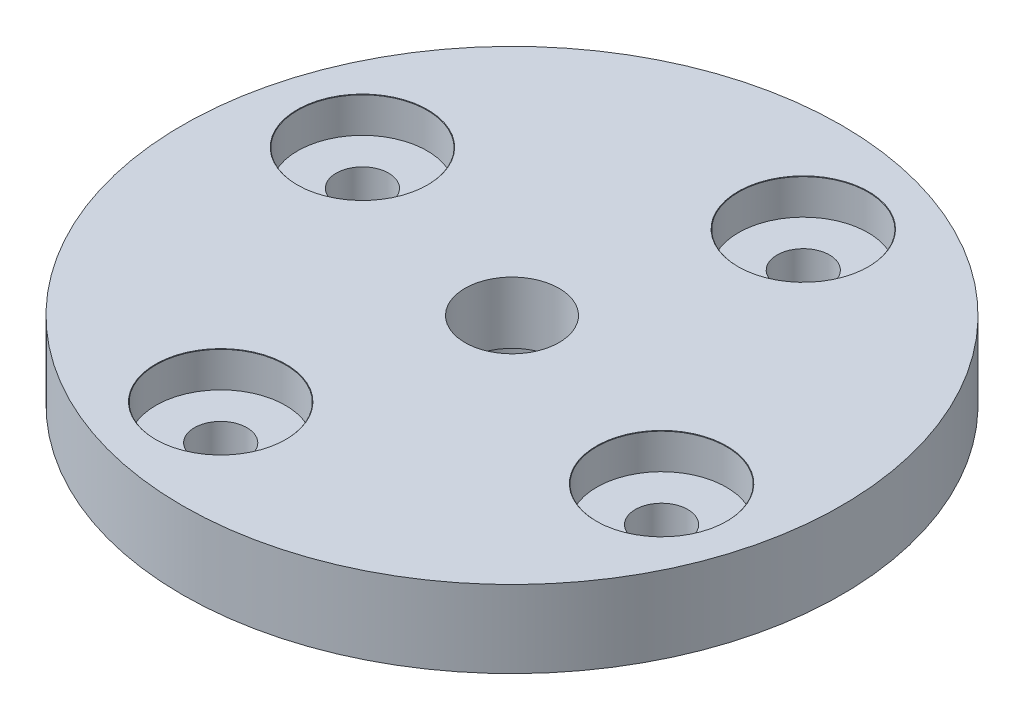
SolidWorks part; units mm, degrees
ref_plane "Front Plane" through (0, 0, 0) normal (0, 0, 1) x (1, 0, 0)
ref_plane "Top Plane" through (0, 0, 0) normal (0, 1, 0) x (1, 0, 0)
ref_plane "Right Plane" through (0, 0, 0) normal (1, 0, 0) x (0, 0, -1)
sketch "Sketch1" plane through (0, 0, 0) normal (0, 0, 1) x (1, 0, 0)
  line L0 (0, 0) -> (0, 7.8872) construction
  line L1 (21.35, 0) -> (21.35, 5)
  line L2 (21.35, 5) -> (3.048, 5)
  line L3 (21.35, 0) -> (4, 0)
  line L4 (4, 0) -> (4, 1)
  line L7 (4, 1) -> (3.048, 1)
  line L8 (3.048, 1) -> (3.048, 5)
  dimension "D1" = 42.7
  dimension "D2" = 5
  dimension "D3" = 6.096
  dimension "D4" = 4
  dimension "D5" = 8
revolve "Revolve1" add sketch "Sketch1" angle 360 about L0
sketch "Sketch2" plane through (0, 5, 0) normal (0, 1, 0) x (1, 0, 0)
  circle A0 centre (4.5902, 14.2804) radius 2.2 construction
  circle A1 centre (-14.2804, 4.5902) radius 2.2 construction
  circle A2 centre (14.2804, -4.5902) radius 2.2 construction
  circle A3 centre (-4.5902, -14.2804) radius 2.2 construction
  circle A4 centre (4.5902, 14.2804) radius 2.2 construction
  circle A5 centre (-14.2804, 4.5902) radius 2.2 construction
  circle A6 centre (14.2804, -4.5902) radius 2.2 construction
  circle A7 centre (-4.5902, -14.2804) radius 2.2 construction
  point P0 (4.5902, 14.2804)
  point P2 (-14.2804, 4.5902)
  point P4 (14.2804, -4.5902)
  point P6 (-4.5902, -14.2804)
hole_wizard "CBORE for M3 Hex Head Machine Screw1" positions "Sketch2" profile "Sketch3" counterbore size "M3" standard "ANSI Metric" end condition through all
sketch "Sketch3" plane through (4.5902, 5, -14.2804) normal (1, 0, 0) x (0, 0, 1)
  line L0 (0, 0) -> (0, 5)
  line L1 (0, 5) -> (1.7, 5)
  line L3 (1.7, 5) -> (1.7, 2.3)
  line L4 (4.2, 2.3) -> (1.7, 2.3)
  line L5 (4.2, 2.3) -> (4.2, 0.025)
  line L6 (4.2, 0.025) -> (4.225, 0)
  line L7 (4.225, 0) -> (0, 0)
  line L8 (-4.2, 0.025) -> (-4.225, 0) construction
  line L11 (0, -6.35) -> (0, 107.95) construction
  dimension "Thru Hole Dia." = 3.4
  dimension "Thru Hole Depth" = 5
  dimension "C'Bore Dia." = 8.4
  dimension "C'Bore Depth" = 2.3
  dimension "Near C'Sink Dia." = 8.45
  dimension "Near C'Sink Angle" = 90
